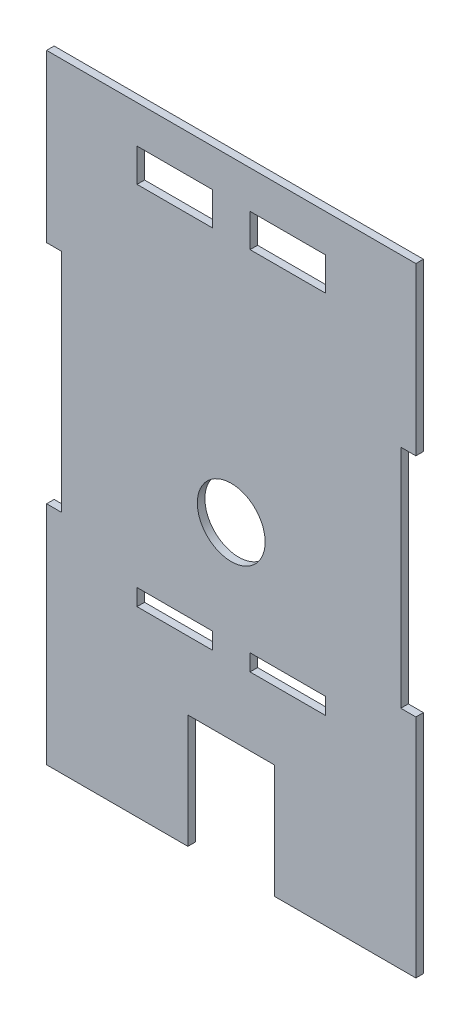
SolidWorks part; units mm, degrees
ref_plane "前视基准面" through (0, 0, 0) normal (0, 0, 1) x (1, 0, 0)
ref_plane "上视基准面" through (0, 0, 0) normal (0, 1, 0) x (1, 0, 0)
ref_plane "右视基准面" through (0, 0, 0) normal (1, 0, 0) x (0, 0, -1)
sketch "Model" plane through (0, 0, 0) normal (0, 0, 1) x (1, 0, 0)
  line L0 (51.031, 63.6241) -> (51.031, 33.6241)
  line L1 (53.031, 85.7257) -> (53.031, 63.6241)
  line L2 (53.031, 33.6241) -> (53.031, 3.6241)
  line L3 (53.031, 63.6241) -> (51.031, 63.6241)
  line L4 (53.031, 33.6241) -> (51.031, 33.6241)
  line L5 (6.031, 63.6241) -> (6.031, 33.6241)
  line L6 (4.031, 33.6241) -> (4.031, 3.6241)
  line L7 (53.031, 33.6241) -> (53.031, 3.6241)
  line L8 (4.031, 63.6241) -> (6.031, 63.6241)
  line L9 (4.031, 33.6241) -> (6.031, 33.6241)
  line L10 (28.531, 18.7241) -> (22.781, 18.7241)
  line L11 (22.781, 18.7241) -> (22.781, 3.6241)
  line L12 (34.281, 3.6241) -> (34.281, 18.7241)
  line L13 (34.281, 18.7241) -> (28.531, 18.7241)
  line L14 (53.031, 3.6241) -> (34.281, 3.6241)
  line L15 (22.781, 3.6241) -> (4.031, 3.6241)
  line L16 (41.031, 27.7971) -> (41.031, 29.9971)
  line L17 (31.031, 27.7971) -> (31.031, 29.9971)
  line L18 (26.031, 27.7971) -> (26.031, 29.9971)
  line L19 (16.031, 27.7971) -> (16.031, 29.9971)
  line L20 (41.031, 29.9971) -> (31.031, 29.9971)
  line L21 (31.031, 27.7971) -> (41.031, 27.7971)
  line L22 (26.031, 29.9971) -> (16.031, 29.9971)
  line L23 (26.031, 27.7971) -> (16.031, 27.7971)
  line L24 (41.031, 80.7257) -> (41.031, 76.3257)
  line L25 (31.031, 76.3257) -> (31.031, 80.7257)
  line L26 (26.031, 80.7257) -> (26.031, 76.3257)
  line L27 (16.031, 80.7257) -> (16.031, 76.3257)
  line L28 (4.031, 85.7257) -> (53.031, 85.7257)
  line L29 (16.031, 80.7257) -> (26.031, 80.7257)
  line L30 (26.031, 76.3257) -> (16.031, 76.3257)
  line L31 (31.031, 80.7257) -> (41.031, 80.7257)
  line L32 (41.031, 76.3257) -> (31.031, 76.3257)
  line L33 (4.031, 85.7257) -> (4.031, 63.6241)
  line L34 (4.031, 76.3257) -> (4.031, 63.6241)
  line L35 (4.031, 33.6241) -> (4.031, 3.6241)
  line L36 (4.031, 33.6241) -> (4.031, 3.6241)
  circle A0 centre (28.531, 43.7241) radius 4.5
extrude "凸台-拉伸1" add sketch "Model" along normal blind 1 contours L28 L33 L8 L5 L9 L6 L15 L11 L10 L13 L12 L14 L2 L4 L0 L3 L1 A0 L24 L32 L25 L31 L26 L30 L27 L29 L18 L23 L19 L22 L21 L17 L20 L16
